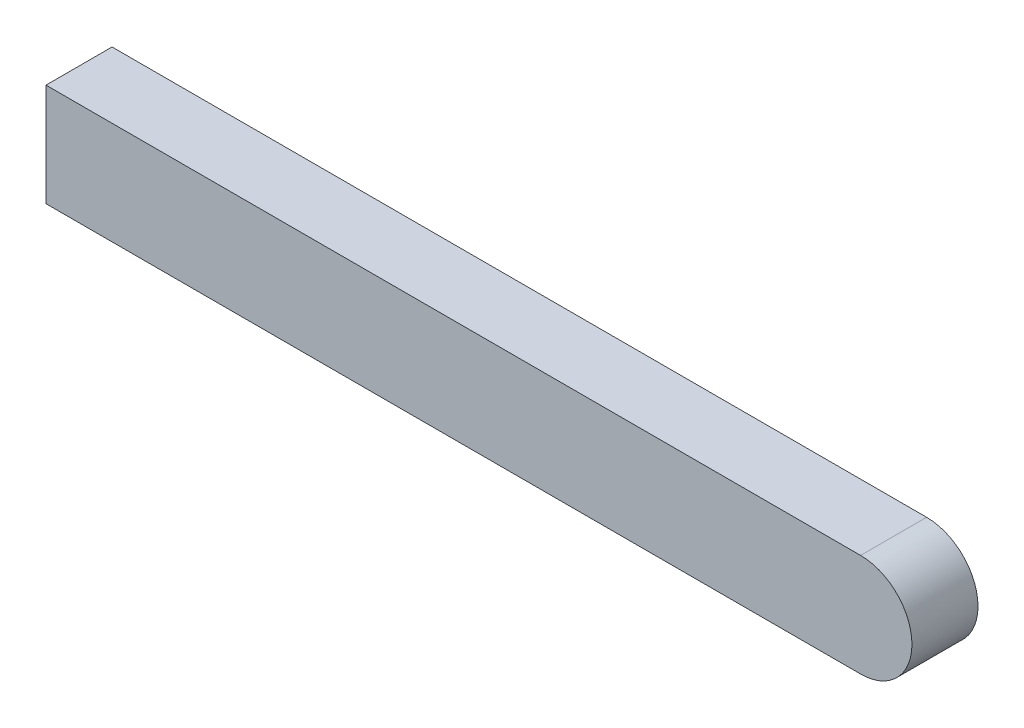
SolidWorks part; units mm, degrees
material "ASTM A36 Steel"
ref_plane "Front Plane" through (0, 0, 0) normal (0, 0, 1) x (1, 0, 0)
ref_plane "Top Plane" through (0, 0, 0) normal (0, 1, 0) x (1, 0, 0)
ref_plane "Right Plane" through (0, 0, 0) normal (1, 0, 0) x (0, 0, -1)
sketch "Sketch1" plane through (0, 0, 0) normal (0, 0, 1) x (1, 0, 0)
  line L0 (-55.5, 0) -> (55.5, 0) construction
  line L1 (-55.5, 7) -> (55.5, 7)
  line L2 (-55.5, -7) -> (55.5, -7)
  arc A0 (-55.5, 7) -> (-55.5, -7) centre (-55.5, 0) ccw
  arc A1 (55.5, -7) -> (55.5, 7) centre (55.5, 0) ccw
  point P2 (0, 0)
  dimension "D2" = 7
  dimension "D1" = 111
extrude "Boss-Extrude1" add sketch "Sketch1" along normal blind 9 contours L1 A1 L2 A0
sketch "Sketch2" plane through (0, 0, 9) normal (0, 0, 1) x (1, 0, 0)
  line L1 (-76.7526, 7) -> (-55.5, 7)
  line L2 (-76.7526, 7) -> (-76.7526, -8.8429)
  line L3 (-76.7526, -8.8429) -> (-55.5, -8.8429)
  line L4 (-55.5, 7) -> (-55.5, -8.8429)
extrude "Cut-Extrude1" cut sketch "Sketch2" against normal blind 10
